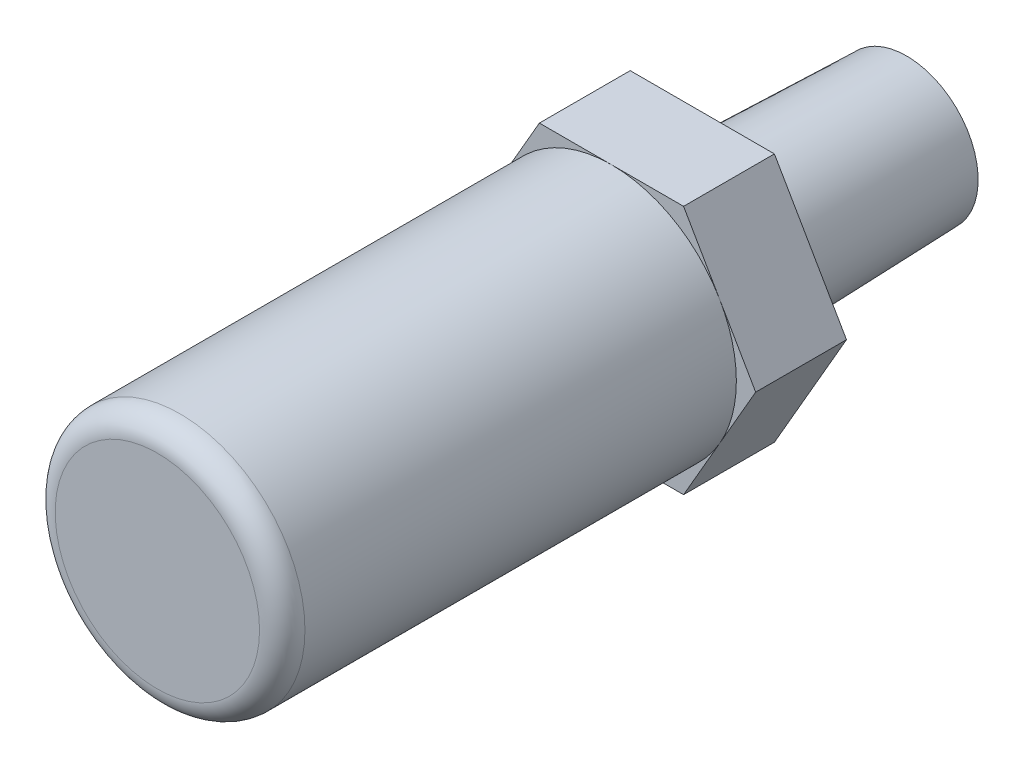
SolidWorks part; units mm, degrees
material "AISI 304"
ref_plane "Front Plane" through (0, 0, 0) normal (0, 0, 1) x (1, 0, 0)
ref_plane "Top Plane" through (0, 0, 0) normal (0, 1, 0) x (1, 0, 0)
ref_plane "Right Plane" through (0, 0, 0) normal (1, 0, 0) x (0, 0, -1)
sketch "Sketch1" plane through (0, 0, 0) normal (0, 0, 1) x (1, 0, 0)
  circle A0 centre (0, 0) radius 11
  dimension "D1" = 22
extrude "Boss-Extrude1" add sketch "Sketch1" against normal blind 40
sketch "Sketch2" plane through (0, 0, -40) normal (0, 0, -1) x (-1, 0, 0)
  line L0 (0, 0) -> (0, -50000) construction
  line L1 (0, 0) -> (50000, 0) construction
  line L2 (6.3509, 11) -> (-6.3509, 11)
  line L3 (-6.3509, 11) -> (-12.7017, 0)
  line L4 (-12.7017, 0) -> (-6.3509, -11)
  line L5 (-6.3509, -11) -> (6.3509, -11)
  line L6 (6.3509, -11) -> (12.7017, 0)
  line L7 (12.7017, 0) -> (6.3509, 11)
  circle A0 centre (0, 0) radius 11 construction
  dimension "D1" = 22
extrude "Boss-Extrude2" add sketch "Sketch2" along normal blind 8
sketch "Sketch6" plane through (0, 0, 0) normal (1, 0, 0) x (0, 0, -1)
  line L0 (0, 0) -> (-50000, 0) construction
  line L1 (48, 6.86) -> (66, 6.2975)
  line L2 (48, 11) -> (48, 0) construction
  line L3 (66, 6.2975) -> (66, 2)
  line L4 (66, 2) -> (48, 2)
  line L5 (48, 2) -> (48, 6.86)
  dimension "D1" = 2
  dimension "D2" = 6.86
  dimension "D3" = 18
  dimension "D4" = 1.79
revolve "Revolve1" add sketch "Sketch6" angle 360 about L0
fillet "Fillet1" radius 2 1 edges at (11, 0, 0)
